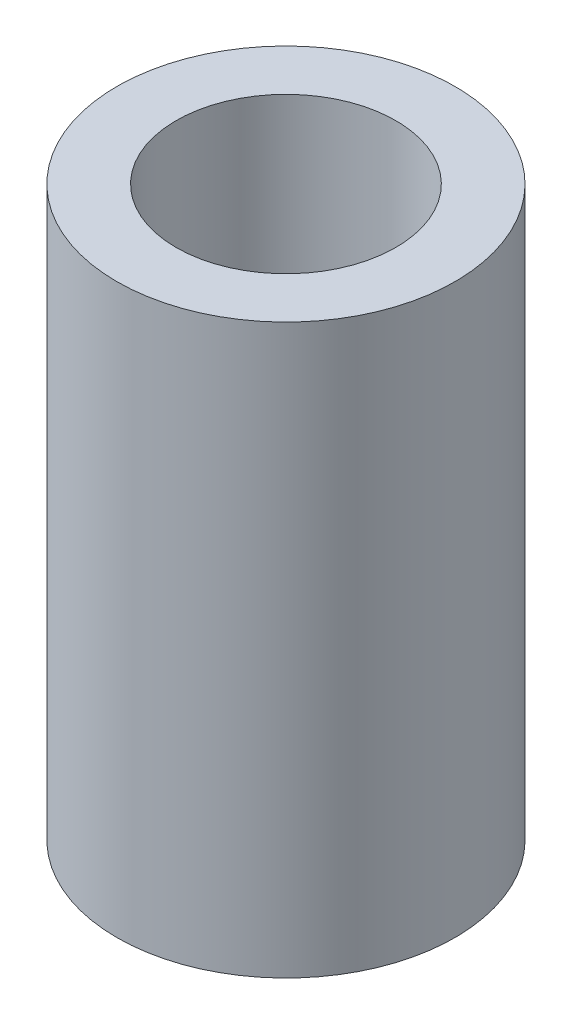
SolidWorks part; units mm, degrees
ref_plane "Front Plane" through (0, 0, 0) normal (0, 0, 1) x (1, 0, 0)
ref_plane "Top Plane" through (0, 0, 0) normal (0, 1, 0) x (1, 0, 0)
ref_plane "Right Plane" through (0, 0, 0) normal (1, 0, 0) x (0, 0, -1)
sketch "Sketch1" plane through (0, 0, 0) normal (0, 1, 0) x (1, 0, 0)
  circle A0 centre (0, 0) radius 1.625
  circle A1 centre (0, 0) radius 2.5
  dimension "D1" = 3.25
  dimension "D2" = 5
extrude "Boss-Extrude1" add sketch "Sketch1" along normal blind 8.4
